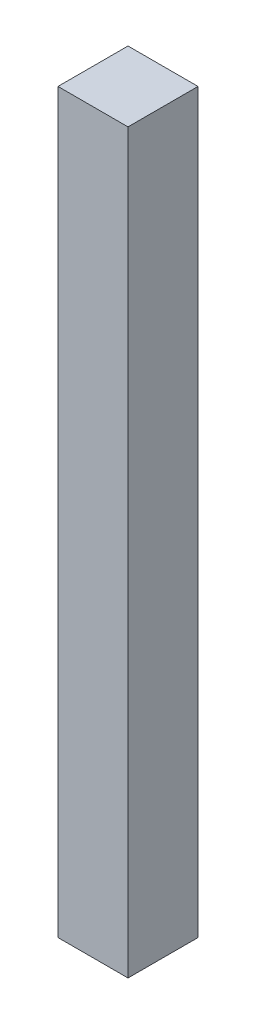
SolidWorks part; units mm, degrees
ref_plane "Front Plane" through (0, 0, 0) normal (0, 0, 1) x (1, 0, 0)
ref_plane "Top Plane" through (0, 0, 0) normal (0, 1, 0) x (1, 0, 0)
ref_plane "Right Plane" through (0, 0, 0) normal (1, 0, 0) x (0, 0, -1)
sketch "Sketch1" plane through (0, 0, 0) normal (0, 1, 0) x (1, 0, 0)
  line L1 (-1.6846, 1.8962) -> (4.0154, 1.8962)
  line L2 (-1.6846, 1.8962) -> (-1.6846, -3.8038)
  line L3 (-1.6846, -3.8038) -> (4.0154, -3.8038)
  line L4 (4.0154, 1.8962) -> (4.0154, -3.8038)
  dimension "D1" = 5.7
  dimension "D2" = 5.7
extrude "Boss-Extrude1" add sketch "Sketch1" along normal blind 60
